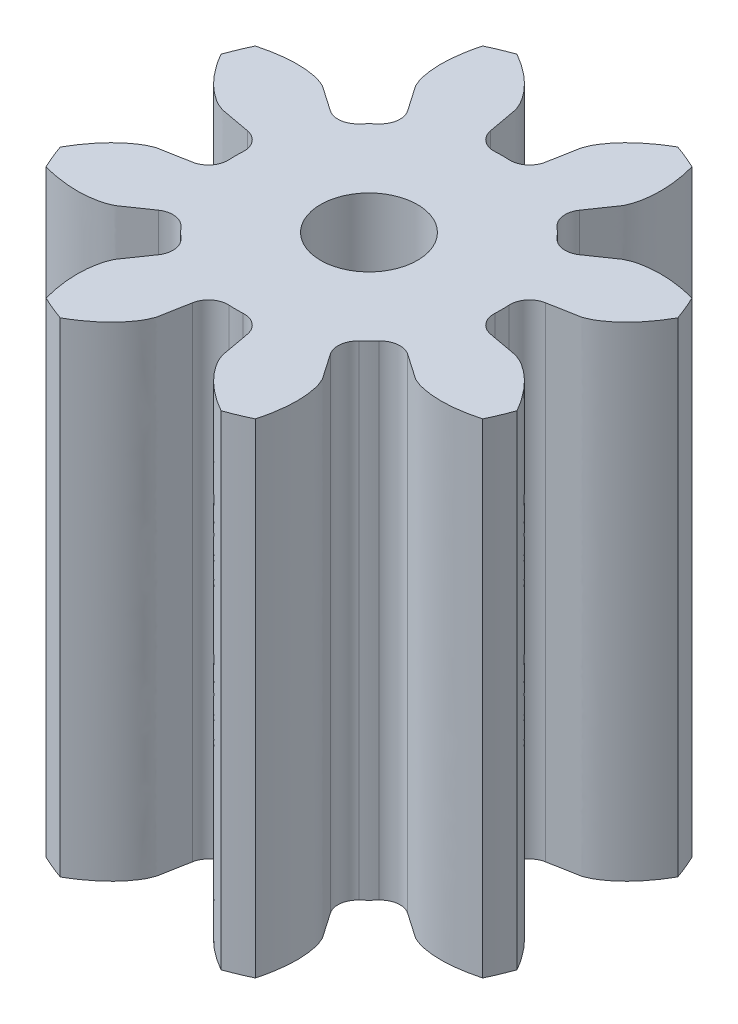
SolidWorks part; units mm, degrees
ref_plane "Plano frontal" through (0, 0, 0) normal (0, 0, 1) x (1, 0, 0)
ref_plane "Plano superior" through (0, 0, 0) normal (0, 1, 0) x (1, 0, 0)
ref_plane "Plano direito" through (0, 0, 0) normal (1, 0, 0) x (0, 0, -1)
ref_plane "Plano1" through (0, -5, 0) normal (0, -1, 0) x (1, 0, 0)
sketch "Esboço1" plane through (0, -5, 0) normal (0, -1, 0) x (1, 0, 0)
  arc A0 (0.8882, -1.2872) -> (0.9193, -1.0225) centre (1.0542, -1.1725) cw
  arc A1 (0.9193, -1.0225) -> (1.0225, -0.9193) centre (0, 0) ccw
  arc A2 (1.0225, -0.9193) -> (1.2872, -0.8882) centre (1.1725, -1.0542) cw
  arc A3 (2.2546, -1.0802) -> (2.3581, -0.8304) centre (0, 0) ccw
  arc A4 (1.5382, -0.2821) -> (1.3731, -0.073) centre (1.5745, -0.0837) cw
  arc A5 (1.3731, -0.073) -> (1.3731, 0.073) centre (0, 0) ccw
  arc A6 (1.3731, 0.073) -> (1.5382, 0.2821) centre (1.5745, 0.0837) cw
  arc A7 (2.3581, 0.8304) -> (2.2546, 1.0802) centre (0, 0) ccw
  arc A8 (1.2872, 0.8882) -> (1.0225, 0.9193) centre (1.1725, 1.0542) cw
  arc A9 (1.0225, 0.9193) -> (0.9193, 1.0225) centre (0, 0) ccw
  arc A10 (0.9193, 1.0225) -> (0.8882, 1.2872) centre (1.0542, 1.1725) cw
  arc A11 (1.0802, 2.2546) -> (0.8304, 2.3581) centre (0, 0) ccw
  arc A12 (0.2821, 1.5382) -> (0.073, 1.3731) centre (0.0837, 1.5745) cw
  arc A13 (0.073, 1.3731) -> (-0.073, 1.3731) centre (0, 0) ccw
  arc A14 (-0.073, 1.3731) -> (-0.2821, 1.5382) centre (-0.0837, 1.5745) cw
  arc A15 (-0.8304, 2.3581) -> (-1.0802, 2.2546) centre (0, 0) ccw
  arc A16 (-0.8882, 1.2872) -> (-0.9193, 1.0225) centre (-1.0542, 1.1725) cw
  arc A17 (-0.9193, 1.0225) -> (-1.0225, 0.9193) centre (0, 0) ccw
  arc A18 (-1.0225, 0.9193) -> (-1.2872, 0.8882) centre (-1.1725, 1.0542) cw
  arc A19 (-2.2546, 1.0802) -> (-2.3581, 0.8304) centre (0, 0) ccw
  arc A20 (-1.5382, 0.2821) -> (-1.3731, 0.073) centre (-1.5745, 0.0837) cw
  arc A21 (-1.3731, 0.073) -> (-1.3731, -0.073) centre (0, 0) ccw
  arc A22 (-1.3731, -0.073) -> (-1.5382, -0.2821) centre (-1.5745, -0.0837) cw
  arc A23 (-2.3581, -0.8304) -> (-2.2546, -1.0802) centre (0, 0) ccw
  arc A24 (-1.2872, -0.8882) -> (-1.0225, -0.9193) centre (-1.1725, -1.0542) cw
  arc A25 (-1.0225, -0.9193) -> (-0.9193, -1.0225) centre (0, 0) ccw
  arc A26 (-0.9193, -1.0225) -> (-0.8882, -1.2872) centre (-1.0542, -1.1725) cw
  arc A27 (-1.0802, -2.2546) -> (-0.8304, -2.3581) centre (0, 0) ccw
  arc A28 (-0.2821, -1.5382) -> (-0.073, -1.3731) centre (-0.0837, -1.5745) cw
  arc A29 (-0.073, -1.3731) -> (0.073, -1.3731) centre (0, 0) ccw
  arc A30 (0.073, -1.3731) -> (0.2821, -1.5382) centre (0.0837, -1.5745) cw
  arc A31 (0.8304, -2.3581) -> (1.0802, -2.2546) centre (0, 0) ccw
  circle A32 centre (0, 0) radius 0.5
  spline S0 degree 3 poles (1.2872, -0.8882) (1.3838, -0.9549) (1.5564, -1.074) (1.5492, -1.0688) (1.6132, -1.0999) (1.6896, -1.1185) (1.8183, -1.1377) (2.004, -1.1357) (2.1699, -1.1037) (2.2546, -1.0802) knots 0.030903 0.030903 0.030903 0.030903 0.091209 0.151514 0.272126 0.392737 0.513349 0.754572 0.995795 0.995795 0.995795 0.995795
  spline S1 degree 3 poles (1.5382, -0.2821) (1.6537, -0.3033) (1.86, -0.3411) (1.8512, -0.3397) (1.9185, -0.363) (1.9856, -0.4038) (2.0902, -0.4813) (2.2201, -0.6139) (2.3148, -0.7539) (2.3581, -0.8304) knots 0.030903 0.030903 0.030903 0.030903 0.091209 0.151514 0.272126 0.392737 0.513349 0.754572 0.995795 0.995795 0.995795 0.995795
  spline S2 degree 3 poles (1.5382, 0.2821) (1.6537, 0.3033) (1.86, 0.3411) (1.8512, 0.3397) (1.9185, 0.363) (1.9856, 0.4038) (2.0902, 0.4813) (2.2201, 0.6139) (2.3148, 0.7539) (2.3581, 0.8304) knots 0.030903 0.030903 0.030903 0.030903 0.091209 0.151514 0.272126 0.392737 0.513349 0.754572 0.995795 0.995795 0.995795 0.995795
  spline S3 degree 3 poles (1.2872, 0.8882) (1.3838, 0.9549) (1.5564, 1.074) (1.5492, 1.0688) (1.6132, 1.0999) (1.6896, 1.1185) (1.8183, 1.1377) (2.004, 1.1357) (2.1699, 1.1037) (2.2546, 1.0802) knots 0.030903 0.030903 0.030903 0.030903 0.091209 0.151514 0.272126 0.392737 0.513349 0.754572 0.995795 0.995795 0.995795 0.995795
  spline S4 degree 3 poles (0.8882, 1.2872) (0.9549, 1.3838) (1.074, 1.5564) (1.0688, 1.5492) (1.0999, 1.6132) (1.1185, 1.6896) (1.1377, 1.8183) (1.1357, 2.004) (1.1037, 2.1699) (1.0802, 2.2546) knots 0.030903 0.030903 0.030903 0.030903 0.091209 0.151514 0.272126 0.392737 0.513349 0.754572 0.995795 0.995795 0.995795 0.995795
  spline S5 degree 3 poles (0.2821, 1.5382) (0.3033, 1.6537) (0.3411, 1.86) (0.3397, 1.8512) (0.363, 1.9185) (0.4038, 1.9856) (0.4813, 2.0902) (0.6139, 2.2201) (0.7539, 2.3148) (0.8304, 2.3581) knots 0.030903 0.030903 0.030903 0.030903 0.091209 0.151514 0.272126 0.392737 0.513349 0.754572 0.995795 0.995795 0.995795 0.995795
  spline S6 degree 3 poles (-0.2821, 1.5382) (-0.3033, 1.6537) (-0.3411, 1.86) (-0.3397, 1.8512) (-0.363, 1.9185) (-0.4038, 1.9856) (-0.4813, 2.0902) (-0.6139, 2.2201) (-0.7539, 2.3148) (-0.8304, 2.3581) knots 0.030903 0.030903 0.030903 0.030903 0.091209 0.151514 0.272126 0.392737 0.513349 0.754572 0.995795 0.995795 0.995795 0.995795
  spline S7 degree 3 poles (-0.8882, 1.2872) (-0.9549, 1.3838) (-1.074, 1.5564) (-1.0688, 1.5492) (-1.0999, 1.6132) (-1.1185, 1.6896) (-1.1377, 1.8183) (-1.1357, 2.004) (-1.1037, 2.1699) (-1.0802, 2.2546) knots 0.030903 0.030903 0.030903 0.030903 0.091209 0.151514 0.272126 0.392737 0.513349 0.754572 0.995795 0.995795 0.995795 0.995795
  spline S8 degree 3 poles (-1.2872, 0.8882) (-1.3838, 0.9549) (-1.5564, 1.074) (-1.5492, 1.0688) (-1.6132, 1.0999) (-1.6896, 1.1185) (-1.8183, 1.1377) (-2.004, 1.1357) (-2.1699, 1.1037) (-2.2546, 1.0802) knots 0.030903 0.030903 0.030903 0.030903 0.091209 0.151514 0.272126 0.392737 0.513349 0.754572 0.995795 0.995795 0.995795 0.995795
  spline S9 degree 3 poles (-1.5382, 0.2821) (-1.6537, 0.3033) (-1.86, 0.3411) (-1.8512, 0.3397) (-1.9185, 0.363) (-1.9856, 0.4038) (-2.0902, 0.4813) (-2.2201, 0.6139) (-2.3148, 0.7539) (-2.3581, 0.8304) knots 0.030903 0.030903 0.030903 0.030903 0.091209 0.151514 0.272126 0.392737 0.513349 0.754572 0.995795 0.995795 0.995795 0.995795
  spline S10 degree 3 poles (-1.5382, -0.2821) (-1.6537, -0.3033) (-1.86, -0.3411) (-1.8512, -0.3397) (-1.9185, -0.363) (-1.9856, -0.4038) (-2.0902, -0.4813) (-2.2201, -0.6139) (-2.3148, -0.7539) (-2.3581, -0.8304) knots 0.030903 0.030903 0.030903 0.030903 0.091209 0.151514 0.272126 0.392737 0.513349 0.754572 0.995795 0.995795 0.995795 0.995795
  spline S11 degree 3 poles (-1.2872, -0.8882) (-1.3838, -0.9549) (-1.5564, -1.074) (-1.5492, -1.0688) (-1.6132, -1.0999) (-1.6896, -1.1185) (-1.8183, -1.1377) (-2.004, -1.1357) (-2.1699, -1.1037) (-2.2546, -1.0802) knots 0.030903 0.030903 0.030903 0.030903 0.091209 0.151514 0.272126 0.392737 0.513349 0.754572 0.995795 0.995795 0.995795 0.995795
  spline S12 degree 3 poles (-0.8882, -1.2872) (-0.9549, -1.3838) (-1.074, -1.5564) (-1.0688, -1.5492) (-1.0999, -1.6132) (-1.1185, -1.6896) (-1.1377, -1.8183) (-1.1357, -2.004) (-1.1037, -2.1699) (-1.0802, -2.2546) knots 0.030903 0.030903 0.030903 0.030903 0.091209 0.151514 0.272126 0.392737 0.513349 0.754572 0.995795 0.995795 0.995795 0.995795
  spline S13 degree 3 poles (-0.2821, -1.5382) (-0.3033, -1.6537) (-0.3411, -1.86) (-0.3397, -1.8512) (-0.363, -1.9185) (-0.4038, -1.9856) (-0.4813, -2.0902) (-0.6139, -2.2201) (-0.7539, -2.3148) (-0.8304, -2.3581) knots 0.030903 0.030903 0.030903 0.030903 0.091209 0.151514 0.272126 0.392737 0.513349 0.754572 0.995795 0.995795 0.995795 0.995795
  spline S14 degree 3 poles (0.2821, -1.5382) (0.3033, -1.6537) (0.3411, -1.86) (0.3397, -1.8512) (0.363, -1.9185) (0.4038, -1.9856) (0.4813, -2.0902) (0.6139, -2.2201) (0.7539, -2.3148) (0.8304, -2.3581) knots 0.030903 0.030903 0.030903 0.030903 0.091209 0.151514 0.272126 0.392737 0.513349 0.754572 0.995795 0.995795 0.995795 0.995795
  spline S15 degree 3 poles (0.8882, -1.2872) (0.9549, -1.3838) (1.074, -1.5564) (1.0688, -1.5492) (1.0999, -1.6132) (1.1185, -1.6896) (1.1377, -1.8183) (1.1357, -2.004) (1.1037, -2.1699) (1.0802, -2.2546) knots 0.030903 0.030903 0.030903 0.030903 0.091209 0.151514 0.272126 0.392737 0.513349 0.754572 0.995795 0.995795 0.995795 0.995795
extrude "Ressalto-extrusão1" add sketch "Esboço1" against normal blind 5
